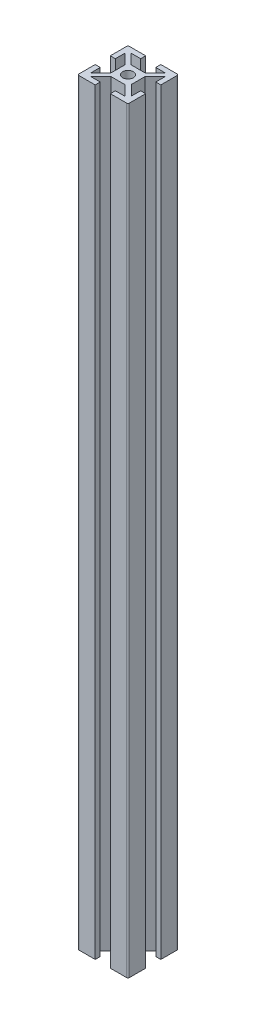
SolidWorks part; units mm, degrees
material "6061 Alloy"
ref_plane "Front Plane" through (0, 0, 0) normal (0, 0, 1) x (1, 0, 0)
ref_plane "Top Plane" through (0, 0, 0) normal (0, 1, 0) x (1, 0, 0)
ref_plane "Right Plane" through (0, 0, 0) normal (1, 0, 0) x (0, 0, -1)
ref_plane "Plane1" through (0, 300, 0) normal (0, 1, 0) x (1, 0, 0)
sketch "Sketch1" plane through (0, 300, 0) normal (0, 1, 0) x (1, 0, 0)
  line L0 (4, 2.7464) -> (8, 6.7464)
  line L1 (8, 6.7464) -> (8, 3)
  line L2 (8, 3) -> (10, 3)
  line L3 (10, 3) -> (10, 9.5)
  line L4 (9.5, 10) -> (3, 10)
  line L5 (3, 10) -> (3, 8)
  line L6 (3, 8) -> (6.8633, 8)
  line L7 (6.8633, 8) -> (2.8633, 4)
  line L8 (2.8633, 4) -> (-2.75, 4)
  line L9 (-2.75, 4) -> (-6.75, 8)
  line L10 (-6.75, 8) -> (-3, 8)
  line L11 (-3, 8) -> (-3, 10)
  line L12 (-3, 10) -> (-9.5, 10)
  line L13 (-10, 9.5) -> (-10, 3)
  line L14 (-10, 3) -> (-8, 3)
  line L15 (-8, 3) -> (-8, 6.75)
  line L16 (-8, 6.75) -> (-4, 2.75)
  line L17 (-4, 2.75) -> (-4, -2.75)
  line L18 (-4, -2.75) -> (-8, -6.75)
  line L19 (-8, -6.75) -> (-8, -3)
  line L20 (-8, -3) -> (-10, -3)
  line L21 (-10, -3) -> (-10, -9.5)
  line L22 (-9.5, -10) -> (-3, -10)
  line L23 (-3, -10) -> (-3, -8)
  line L24 (-3, -8) -> (-6.75, -8)
  line L25 (-6.75, -8) -> (-2.75, -4)
  line L26 (-2.75, -4) -> (2.8685, -4)
  line L27 (2.8685, -4) -> (6.8685, -8)
  line L28 (6.8685, -8) -> (3, -8)
  line L29 (3, -8) -> (3, -10)
  line L30 (3, -10) -> (9.5, -10)
  line L31 (10, -9.5) -> (10, -3)
  line L32 (10, -3) -> (8, -3)
  line L33 (8, -3) -> (8, -6.6652)
  line L34 (8, -6.6652) -> (4, -2.6652)
  line L35 (4, -2.6652) -> (4, 2.7464)
  arc A0 (10, 9.5) -> (9.5, 10) centre (9.5, 9.5) ccw
  arc A1 (-9.5, 10) -> (-10, 9.5) centre (-9.5, 9.5) ccw
  arc A2 (-10, -9.5) -> (-9.5, -10) centre (-9.5, -9.5) ccw
  arc A3 (9.5, -10) -> (10, -9.5) centre (9.5, -9.5) ccw
  circle A4 centre (0, 0) radius 2.1
extrude "Boss-Extrude1" add sketch "Sketch1" against normal blind 300
ref_plane "Plane2" through (0, 0, 0) normal (0, 0, 1) x (1, 0, 0)
ref_plane "Plane3" through (0, 0, 0) normal (1, 0, 0) x (0, 0, -1)
